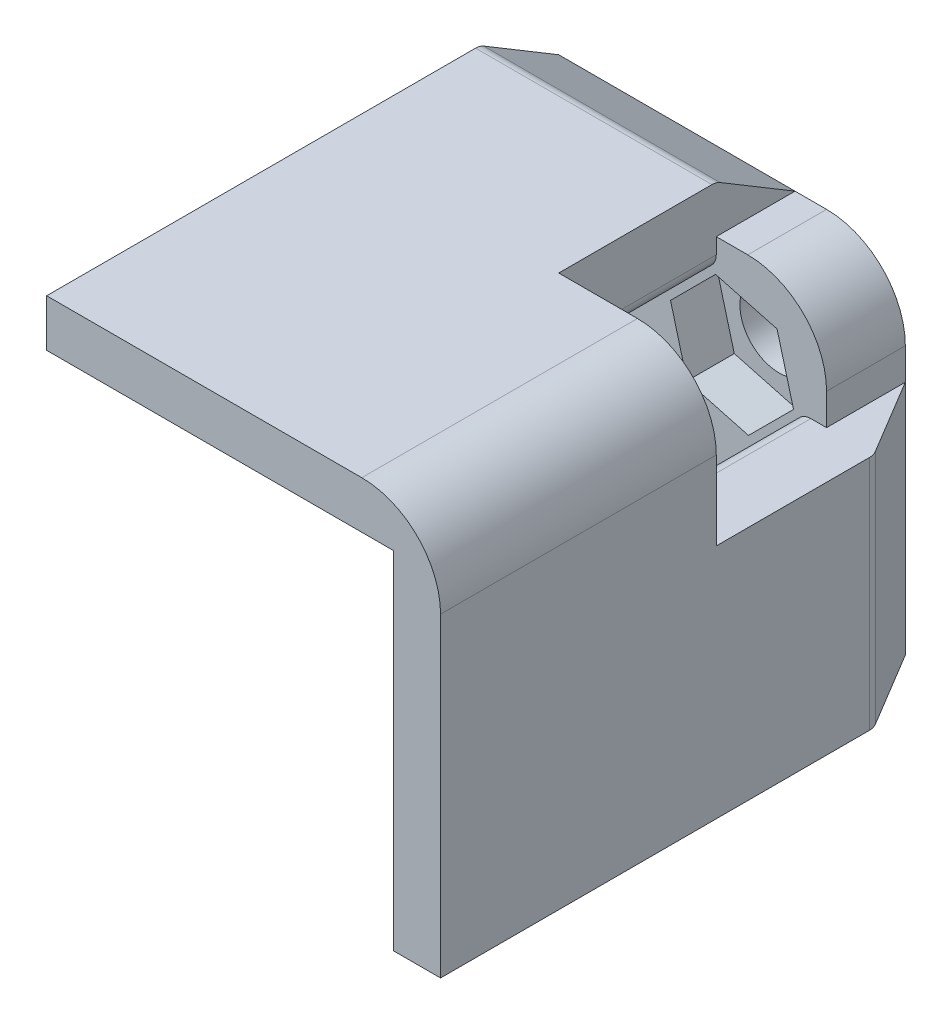
SolidWorks part; units mm, degrees
ref_plane "Plan de face" through (0, 0, 0) normal (0, 0, 1) x (1, 0, 0)
ref_plane "Plan de dessus" through (0, 0, 0) normal (0, 1, 0) x (1, 0, 0)
ref_plane "Plan de droite" through (0, 0, 0) normal (1, 0, 0) x (0, 0, -1)
sketch "Esquisse1" plane through (0, 0, 0) normal (0, 0, 1) x (1, 0, 0)
  line L0 (-11.0124, 11.8443) -> (13.9876, 11.8443)
  line L1 (13.9876, 11.8443) -> (13.9876, -13.1557)
  line L2 (13.9876, -13.1557) -> (8.9876, -13.1557)
  line L3 (8.9876, -13.1557) -> (8.9876, 6.8443)
  line L4 (8.9876, 6.8443) -> (-11.0124, 6.8443)
  line L5 (-11.0124, 6.8443) -> (-11.0124, 11.8443)
  dimension "D1" = 5
  dimension "D2" = 20
extrude "Boss.-Extru.4" add sketch "Esquisse1" along normal blind 25
sketch "Esquisse6" plane through (0, 0, 25) normal (0, 0, 1) x (1, 0, 0)
  line L0 (10.9876, -13.1557) -> (13.9876, -13.1557)
  line L1 (8.9876, -13.1557) -> (13.9876, -13.1557) construction
  line L2 (13.9876, -13.1557) -> (13.9876, 11.8443)
  line L3 (13.9876, 11.8443) -> (-11.0124, 11.8443)
  line L4 (-11.0124, 11.8443) -> (-11.0124, 8.8443)
  line L5 (-11.0124, 11.8443) -> (-11.0124, 6.8443) construction
  line L6 (-11.0124, 8.8443) -> (10.9876, 8.8443)
  line L7 (10.9876, 8.8443) -> (10.9876, -13.1557)
  dimension "D1" = 3
extrude "Boss.-Extru.5" add sketch "Esquisse6" along normal blind 2.5
sketch "Esquisse7" plane through (0, 0, 0) normal (0, 0, -1) x (-1, 0, 0)
  line L0 (11.0124, 6.8443) -> (-8.9876, -13.1557)
  line L1 (-8.9876, -13.1557) -> (-13.9876, -13.1557)
  line L2 (-13.9876, -13.1557) -> (-13.9876, 11.8443)
  line L3 (-13.9876, 11.8443) -> (11.0124, 11.8443)
  line L4 (11.0124, 11.8443) -> (11.0124, 6.8443)
extrude "Boss.-Extru.6" add sketch "Esquisse7" along normal blind 5
sketch "Esquisse8" plane through (13.9876, 0, 0) normal (1, 0, 0) x (0, 0, -1)
  line L0 (-27.5, 11.8443) -> (5, 11.8443) construction
  line L1 (-10, 11.8443) -> (0, 11.8443)
  line L2 (-10, 11.8443) -> (-10, 1.8443)
  line L3 (-10, 1.8443) -> (0, 1.8443)
  line L4 (0, 11.8443) -> (0, 1.8443)
  line L5 (0, 6.8443) -> (0, -13.1557) construction
  dimension "D1" = 10
  dimension "D2" = 10
extrude "Enlèv. mat.-Extru.3" cut sketch "Esquisse8" against normal blind 10
sketch "Esquisse14" plane through (-11.0124, 0, 0) normal (-1, 0, 0) x (0, 0, 1)
  line L0 (27.5, 8.8443) -> (25, 8.8443) construction
  line L1 (-5, 11.8443) -> (0, 11.8443)
  line L2 (-5, 11.8443) -> (-5, 8.8443)
  line L3 (-5, 8.8443) -> (0, 8.8443)
  line L4 (0, 11.8443) -> (0, 8.8443)
  line L6 (0, 6.8443) -> (0, 11.8443) construction
extrude "Enlèv. mat.-Extru.13" cut sketch "Esquisse14" against normal up to vertex
sketch "Esquisse15" plane through (0, -13.1557, 0) normal (0, -1, 0) x (-1, 0, 0)
  line L0 (-10.9876, -27.5) -> (-10.9876, -25) construction
  line L1 (-13.9876, 5) -> (-10.9876, 5)
  line L2 (-13.9876, 5) -> (-13.9876, 0)
  line L3 (-13.9876, 0) -> (-10.9876, 0)
  line L4 (-10.9876, 5) -> (-10.9876, 0)
  line L5 (-13.9876, 0) -> (-3.9876, 0) construction
extrude "Enlèv. mat.-Extru.14" cut sketch "Esquisse15" against normal up to vertex
sketch "Esquisse16" plane through (0, -13.1557, 0) normal (0, -1, 0) x (-1, 0, 0)
  line L0 (-10.9876, 0) -> (-13.9876, 0)
  line L1 (-13.9876, 0) -> (-10.9876, 5)
  line L2 (-10.9876, 5) -> (-10.9876, 0)
extrude "Boss.-Extru.8" add sketch "Esquisse16" against normal up to vertex
sketch "Esquisse17" plane through (-11.0124, 0, 0) normal (-1, 0, 0) x (0, 0, 1)
  line L0 (-5, 8.8443) -> (0, 11.8443)
  line L1 (0, 11.8443) -> (0, 8.8443)
  line L2 (0, 8.8443) -> (-5, 8.8443)
extrude "Boss.-Extru.9" add sketch "Esquisse17" against normal up to vertex (15 mm away) up to point (3.9876, 8.8443, 0)
fillet "Congé16" radius 5 2 edges at (13.9876, 11.8443, 18.75) (10.9876, 8.8443, -2.5)
sketch "Esquisse18" plane through (0, 0, 0) normal (0, 0, 1) x (1, 0, 0)
  line L0 (5.9876, 8.8443) -> (3.9876, 8.8443) construction
  line L1 (2.1299, -0.0135) -> (6.0336, -1.0595)
  line L2 (6.0336, -1.0595) -> (8.8914, 1.7983)
  line L3 (8.8914, 1.7983) -> (7.8454, 5.702)
  line L4 (7.8454, 5.702) -> (3.9416, 6.748)
  line L5 (3.9416, 6.748) -> (1.0839, 3.8903)
  line L6 (1.0839, 3.8903) -> (2.1299, -0.0135)
  line L7 (10.9876, 1.8443) -> (10.9876, -13.1557) construction
  line L8 (-1.0124, -3.1557) -> (9.5232, 7.3798) construction
  line L9 (8.9876, -13.1557) -> (-11.0124, 6.8443) construction
  circle A0 centre (4.9876, 2.8443) radius 3.5 construction
  arc A1 (10.9876, 3.8443) -> (5.9876, 8.8443) centre (5.9876, 3.8443) ccw construction
  point P17 (9.5232, 7.3798)
  dimension "D1" = 6
  dimension "D2" = 6
  dimension "D3" = 7
sketch "Esquisse20" plane through (0, 0, -3) normal (0, 0, 1) x (1, 0, 0)
  line L0 (2.1299, -0.0135) -> (7.8454, 5.702) construction
  circle A0 centre (4.9876, 2.8443) radius 2.5
  point P7 (4.9876, 2.8443)
  dimension "D1" = 5
extrude "Enlèv. mat.-Extru.16" cut sketch "Esquisse20" against normal up to vertex (2 mm away)
extrude "Enlèv. mat.-Extru.17" cut sketch "Esquisse18" against normal blind 3
fillet "Congé31" radius 1 2 edges at (8.9876, 1.8443, 5) (3.9876, 6.8443, 5)
fillet "Congé37" radius 1 2 edges at (-3.5124, 11.8443, 0) (13.9876, -5.6557, 0)
